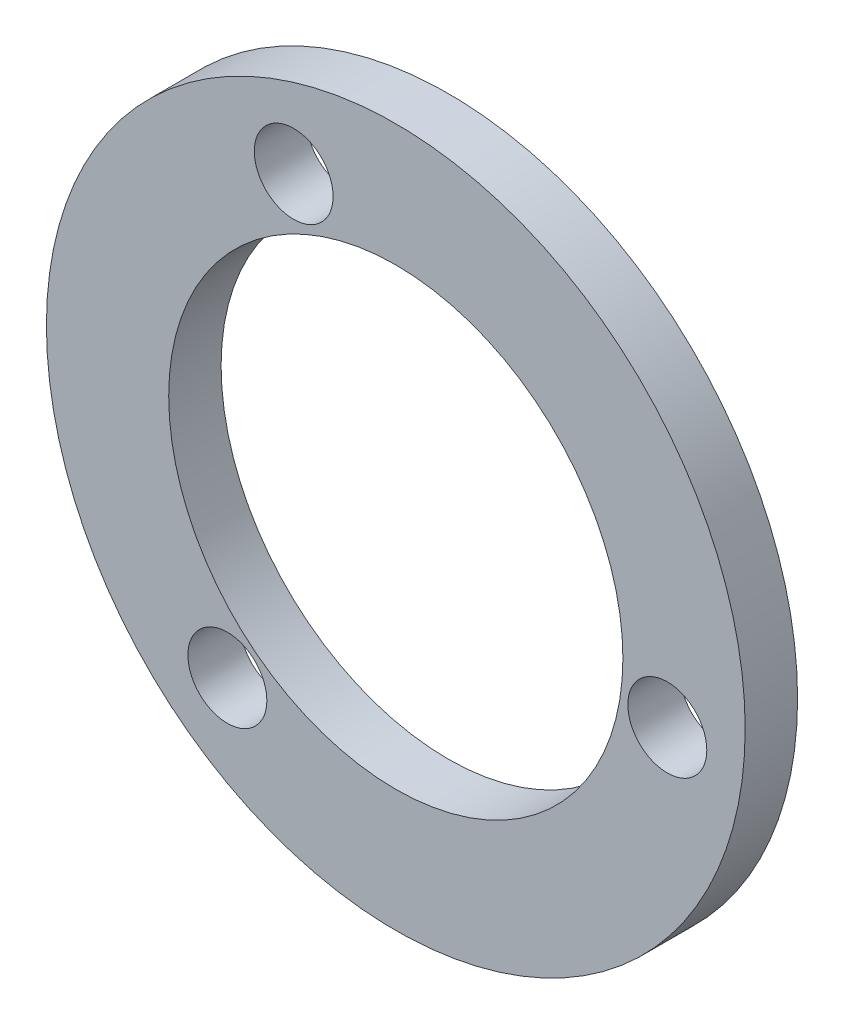
SolidWorks part; units mm, degrees
ref_plane "Front Plane" through (0, 0, 0) normal (0, 0, 1) x (1, 0, 0)
ref_plane "Top Plane" through (0, 0, 0) normal (0, 1, 0) x (1, 0, 0)
ref_plane "Right Plane" through (0, 0, 0) normal (1, 0, 0) x (0, 0, -1)
sketch "Sketch1" plane through (0, 0, 0) normal (0, 0, 1) x (1, 0, 0)
  circle A0 centre (197.5995, 433.8755) radius 13
  circle A1 centre (197.5995, 433.8755) radius 20
  circle A2 centre (191.7545, 448.4649) radius 2.2552 construction
  circle A3 centre (213.1417, 431.7183) radius 2.2598 construction
  circle A4 centre (187.9587, 421.588) radius 2.2602 construction
  circle A5 centre (191.7545, 448.4649) radius 2.2552
  circle A6 centre (213.1417, 431.7183) radius 2.2598
  circle A7 centre (187.9587, 421.588) radius 2.2602
  dimension "D1" = 26
  dimension "D2" = 40
extrude "Boss-Extrude1" add sketch "Sketch1" along normal blind 3
